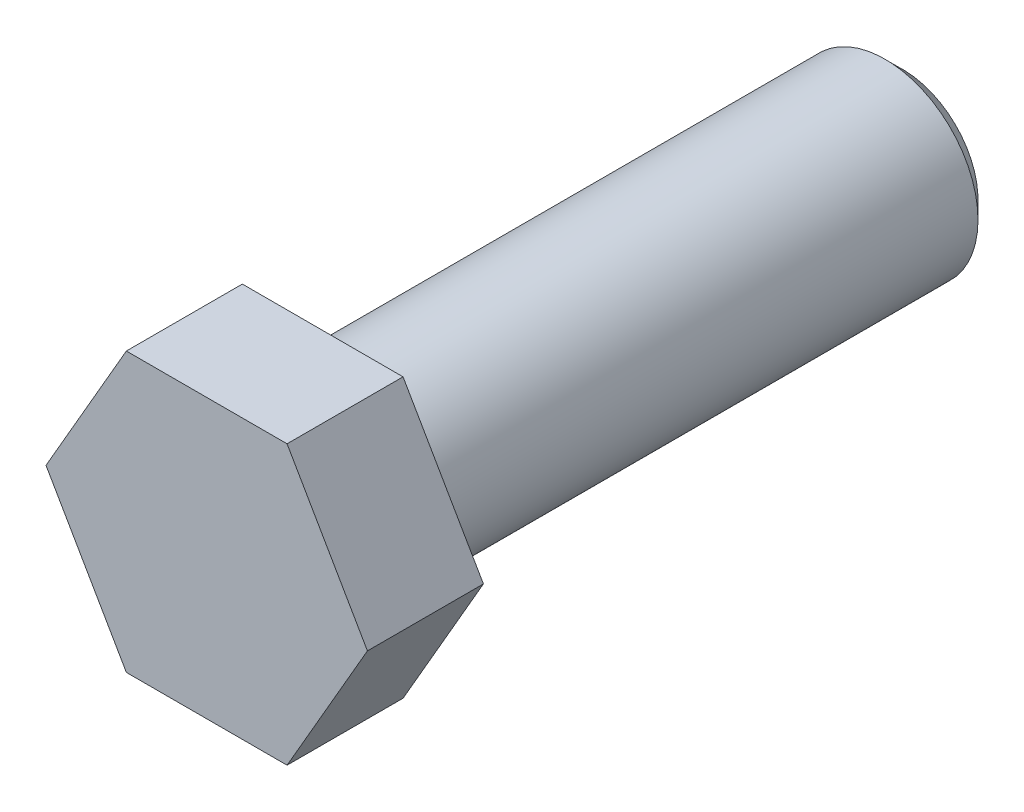
SolidWorks part; units mm, degrees
ref_plane "Plane1" through (0, 0, 0) normal (0, 0, 1) x (1, 0, 0)
ref_plane "MSC_PF1" through (0, 0, 0) normal (0, 1, 0) x (1, 0, 0)
ref_plane "Plane3" through (0, 0, 0) normal (1, 0, 0) x (0, 0, -1)
sketch "Sketch1" plane through (0, 0, 0) normal (0, 0, 1) x (1, 0, 0)
  line L0 (0, 0) -> (1, 0) construction
  line L1 (-6.9282, 12) -> (6.9282, 12)
  line L2 (-6.9282, -12) -> (6.9282, -12)
  line L3 (6.9282, 12) -> (13.8564, 0)
  line L4 (13.8564, 0) -> (6.9282, -12)
  line L5 (-6.9282, 12) -> (-13.8564, 0)
  line L6 (-13.8564, 0) -> (-6.9282, -12)
  circle A0 centre (0, 0) radius 12 construction
  dimension "P" = 1
  dimension "s" = 24
extrude "Base-Extrude" add sketch "Sketch1" along normal blind 10
sketch "Sketch3" plane through (0, 0, 0) normal (0, 0, -1) x (-1, 0, 0)
  circle A0 centre (0, 0) radius 8
  dimension "_d" = 16
extrude "Boss-Extrude1" add sketch "Sketch3" along normal blind 50
cosmetic thread "Условное изображение резьбы2" parameters "D2"=15
chamfer "Chamfer1" distance 1.5 angle 45 1 edges at (-8, 0, -50)
